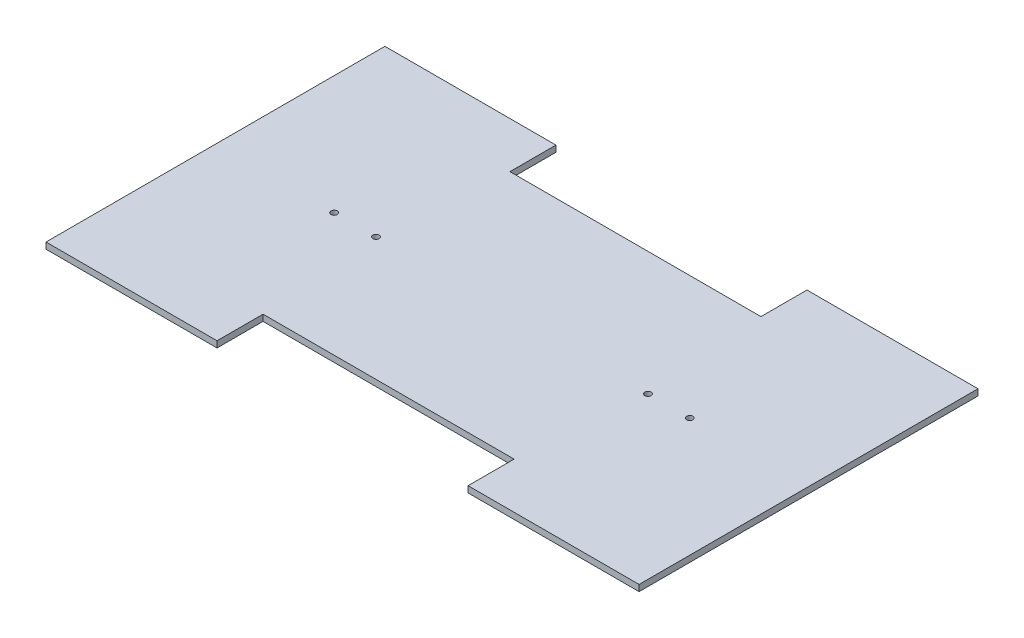
SolidWorks part; units mm, degrees
ref_plane "Front Plane" through (0, 0, 0) normal (0, 0, 1) x (1, 0, 0)
ref_plane "Top Plane" through (0, 0, 0) normal (0, 1, 0) x (1, 0, 0)
ref_plane "Right Plane" through (0, 0, 0) normal (1, 0, 0) x (0, 0, -1)
sketch "Sketch1" plane through (0, 0, 0) normal (0, 1, 0) x (1, 0, 0)
  line L1 (-141.75, 81) -> (141.75, 81)
  line L2 (-141.75, 81) -> (-141.75, -81)
  line L3 (-141.75, -81) -> (141.75, -81)
  line L4 (141.75, 81) -> (141.75, -81)
  line L5 (-141.75, 81) -> (141.75, -81) construction
  line L6 (-141.75, -81) -> (141.75, 81) construction
  point P0 (0, 0)
extrude "Boss-Extrude1" add sketch "Sketch1" along normal blind 3
sketch "Sketch2" plane through (0, 3, 0) normal (0, 1, 0) x (1, 0, 0)
  line L0 (-141.75, -81) -> (141.75, -81) construction
  line L2 (-60, -81) -> (-60, -59)
  line L3 (-60, -59) -> (60, -59)
  line L4 (60, -81) -> (60, -59)
  line L5 (-1.65, 0) -> (1.65, 0) construction
  line L6 (-60, 81) -> (60, 81)
  line L7 (-60, -81) -> (60, -81)
  line L8 (60, 81) -> (60, 59)
  line L9 (-60, 59) -> (60, 59)
  line L10 (-60, 81) -> (-60, 59)
  point P0 (0, -81)
  dimension "D1" = 22
  dimension "D2" = 120
  dimension "D3" = 60
extrude "Cut-Extrude1" cut sketch "Sketch2" against normal blind 3
sketch "Sketch3" plane through (0, 3, 0) normal (0, 1, 0) x (1, 0, 0)
  line L0 (0, 0) -> (0, 59) construction
  line L1 (-60, 59) -> (60, 59) construction
  line L2 (0, 0) -> (130, 0) construction
  line L3 (0, 0) -> (-65, 0) construction
  line L4 (-65, 0) -> (-85, 0) construction
  circle A4 centre (-65, 0) radius 1.5
  circle A5 centre (-85, 0) radius 1.5
  circle A6 centre (65, 0) radius 1.5
  circle A7 centre (85, 0) radius 1.5
  point P5 (-32.5, 0)
extrude "Cut-Extrude2" [suppressed] cut sketch "Sketch3" against normal blind 3
sketch "Sketch4" plane through (0, 3, 0) normal (0, 1, 0) x (1, 0, 0)
  line L0 (0, 0) -> (130, 0) construction
  circle A0 centre (-85, 0) radius 1.5
  circle A1 centre (-65, 0) radius 1.5
  circle A2 centre (65, 0) radius 1.5
  circle A3 centre (85, 0) radius 1.5
extrude "Cut-Extrude3" cut sketch "Sketch4" against normal through all both
sketch "Sketch5" plane through (0, 3, 0) normal (0, 1, 0) x (1, 0, 0)
  line L0 (0, 0) -> (-65, 0) construction
  line L1 (-65, 0) -> (-85, 0) construction
  line L2 (0, 0) -> (65, 0) construction
  line L3 (65, 0) -> (85, 0) construction
